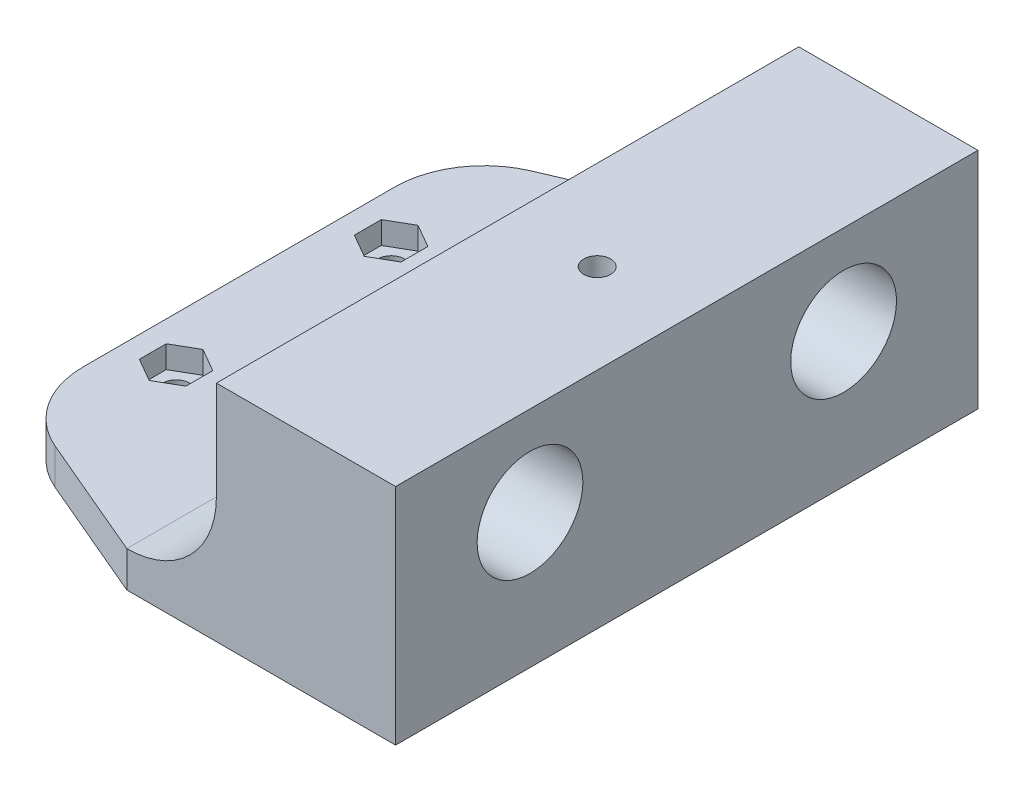
SolidWorks part; units mm, degrees
ref_plane "Front Plane" through (0, 0, 0) normal (0, 0, 1) x (1, 0, 0)
ref_plane "Top Plane" through (0, 0, 0) normal (0, 1, 0) x (1, 0, 0)
ref_plane "Right Plane" through (0, 0, 0) normal (1, 0, 0) x (0, 0, -1)
sketch "Sketch1" plane through (0, 0, 0) normal (0, 0, 1) x (1, 0, 0)
  line L0 (0, 0) -> (0, 25) construction
  line L2 (-40, 0) -> (-40, 4)
  line L3 (-40, 4) -> (-20, 4)
  line L4 (-10, 14) -> (-10, 25)
  line L5 (-10, 25) -> (10, 25)
  line L6 (10, 14) -> (10, 25)
  line L9 (10, 14) -> (10, 0)
  line L10 (10, 0) -> (-40, 0)
  arc A0 (-20, 4) -> (-10, 14) centre (-20, 14) ccw
  point P13 (-10, 4)
  point P16 (10, 4)
  dimension "D4" = 10
  dimension "D1" = 25
  dimension "D2" = 50
  dimension "D3" = 20
  dimension "D6" = 4
extrude "Boss-Extrude1" add sketch "Sketch1" along normal mid plane 65
sketch "Sketch2" plane through (10, 0, 0) normal (1, 0, 0) x (0, 0, -1)
  line L0 (0, 0) -> (0, 25) construction
  line L1 (-32.5, 0) -> (32.5, 0) construction
  line L2 (-32.5, 25) -> (32.5, 25) construction
  circle A0 centre (-17.5, 15) radius 5.9
  circle A1 centre (17.5, 15) radius 5.9
  dimension "D1" = 11.8
  dimension "D2" = 35
  dimension "D3" = 15
extrude "Cut-Extrude1" cut sketch "Sketch2" against normal through all both and the other way through all
sketch "Sketch3" plane through (0, 0, 0) normal (0, -1, 0) x (1, 0, 0)
  line L0 (-35, -32.5) -> (-35, 32.5) construction
  line L1 (-40, -32.5) -> (10, -32.5) construction
  line L2 (-40, 32.5) -> (10, 32.5) construction
  line L3 (0, 0) -> (-40, 0) construction
  line L4 (-40, 32.5) -> (-40, -32.5) construction
  circle A0 centre (-35, 12) radius 1.5
  circle A1 centre (-35, -12) radius 1.5
  dimension "D1" = 3
  dimension "D3" = 24
  dimension "D2" = 5
extrude "Cut-Extrude2" cut sketch "Sketch3" against normal through all both and the other way through all
sketch "Sketch4" plane through (0, 25, 0) normal (0, 1, 0) x (1, 0, 0)
  line L0 (0, -32.5) -> (0, 32.5) construction
  line L1 (10, -32.5) -> (-10, -32.5) construction
  line L2 (10, 32.5) -> (-10, 32.5) construction
  line L3 (10, -32.5) -> (10, 32.5) construction
  circle A0 centre (0, 0) radius 1.5
  dimension "D1" = 3
  dimension "D2" = 10
extrude "Cut-Extrude3" cut sketch "Sketch4" against normal through all both and the other way through all
sketch "Sketch5" plane through (0, 4, 0) normal (0, 1, 0) x (1, 0, 0)
  line L0 (-40, -32.5) -> (-40, 32.5) construction
  line L1 (-32.4019, -10.5) -> (-35, -9)
  line L2 (-35, -9) -> (-37.5981, -10.5)
  line L3 (-37.5981, -10.5) -> (-37.5981, -13.5)
  line L4 (-37.5981, -13.5) -> (-35, -15)
  line L5 (-35, -15) -> (-32.4019, -13.5)
  line L6 (-32.4019, -13.5) -> (-32.4019, -10.5)
  line L7 (-32.4019, 10.5) -> (-32.4019, 13.5)
  line L8 (-32.4019, 13.5) -> (-35, 15)
  line L9 (-35, 15) -> (-37.5981, 13.5)
  line L10 (-37.5981, 13.5) -> (-37.5981, 10.5)
  line L11 (-37.5981, 10.5) -> (-35, 9)
  line L12 (-35, 9) -> (-32.4019, 10.5)
  circle A0 centre (-35, -12) radius 2.5981 construction
  circle A1 centre (-35, 12) radius 2.5981 construction
  dimension "D1" = 3
  dimension "D2" = 3
extrude "Cut-Extrude4" cut sketch "Sketch5" against normal blind 2.5
sketch "Sketch6" plane through (0, 4, 0) normal (0, 1, 0) x (1, 0, 0)
  line L0 (-20, -32.5) -> (-40, -24)
  line L1 (-40, -32.5) -> (-40, 32.5) construction
  line L2 (-40, 0) -> (-20, 0) construction
  line L3 (-20, -32.5) -> (-20, 32.5) construction
  line L4 (-20, 32.5) -> (-40, 24)
  line L5 (-40, -24) -> (-40, -32.5)
  line L6 (-40, -32.5) -> (-20, -32.5)
  line L7 (-40, 24) -> (-40, 32.5)
  line L8 (-40, 32.5) -> (-20, 32.5)
  dimension "D1" = 48
extrude "Cut-Extrude5" cut sketch "Sketch6" against normal through all both and the other way through all
fillet "Fillet1" radius 10 2 edges at (-40, 2, -24) (-40, 2, 24)
